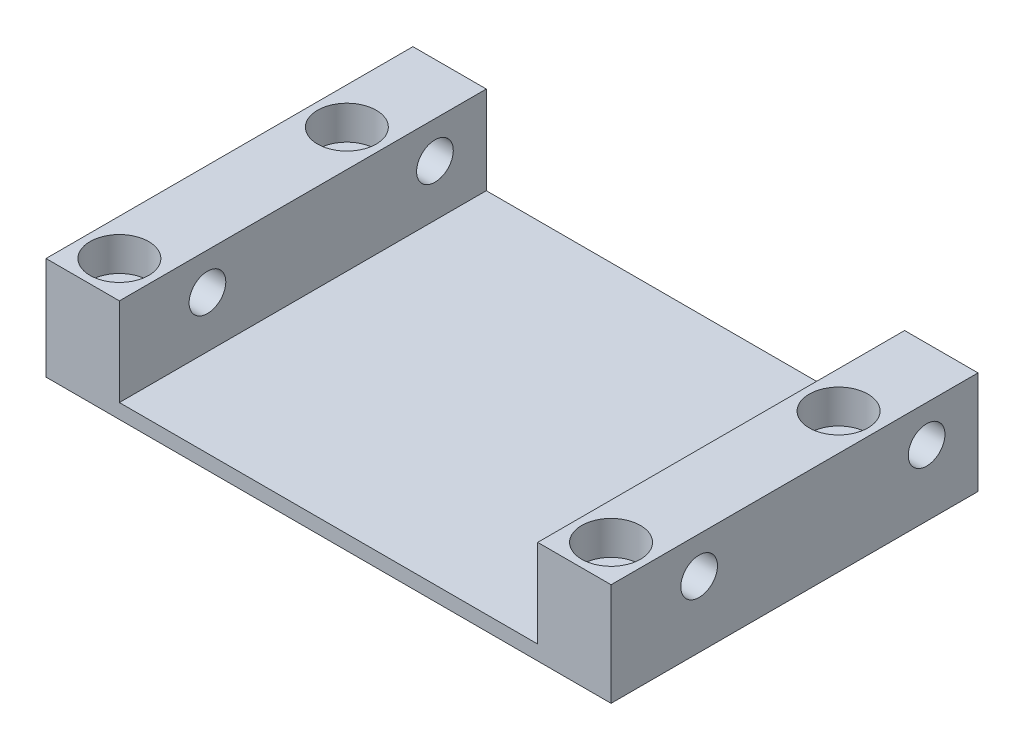
SolidWorks part; units mm, degrees
material "1060 合金"
ref_plane "前视基准面" through (0, 0, 0) normal (0, 0, 1) x (1, 0, 0)
ref_plane "上视基准面" through (0, 0, 0) normal (0, 1, 0) x (1, 0, 0)
ref_plane "右视基准面" through (0, 0, 0) normal (1, 0, 0) x (0, 0, -1)
sketch "草图1" plane through (0, 0, 0) normal (0, 0, 1) x (1, 0, 0)
  line L0 (0, 0) -> (0, 27.6431) construction
  line L3 (-28.5, 2) -> (-28.5, 14)
  line L4 (-28.5, 14) -> (-38.5, 14)
  line L5 (-38.5, 14) -> (-38.5, 0)
  line L10 (38.5, 14) -> (38.5, 0)
  line L11 (28.5, 14) -> (38.5, 14)
  line L12 (28.5, 2) -> (28.5, 14)
  line L13 (-28.5, 2) -> (28.5, 2)
  line L14 (38.5, 0) -> (-38.5, 0)
  dimension "D1" = 57
  dimension "D2" = 2
  dimension "D3" = 12
  dimension "D6" = 10
extrude "凸台-拉伸1" add sketch "草图1" against normal mid plane 50
sketch "草图4" plane through (0, 0, 0) normal (1, 0, 0) x (0, 0, -1)
  line L1 (25, 0) -> (25, 14) construction
  line L2 (25, 14) -> (-25, 14) construction
  circle A0 centre (18, 9) radius 2.5
  circle A2 centre (18, 9) radius 2.5 construction
  circle A4 centre (-13, 9) radius 2.5 construction
  circle A5 centre (-13, 9) radius 2.5
  dimension "D3" = 5
  dimension "D1" = 5
  dimension "D2" = 31
  dimension "D4" = 7
extrude "切除-拉伸1" cut sketch "草图4" against normal mid plane 100
hole_wizard "打孔尺寸根据内六角圆柱头螺钉的类型2" positions "草图10" profile "草图9" counterbore size "M4" standard "GB" end condition through all
sketch "草图10" plane through (0, 14, 0) normal (0, 1, 0) x (-1, 0, 0)
  line L0 (38.5, 13) -> (28.5, 13) construction
  line L1 (38.5, -18) -> (28.5, -18) construction
  line L2 (38.5, -25) -> (38.5, 25) construction
  point P0 (33.5, -11)
  point P1 (33.5, 20)
  dimension "D1" = 7
  dimension "D2" = 7
  dimension "D3" = 5
sketch "草图9" plane through (-33.5, 14, -11) normal (1, 0, 0) x (0, 0, 1)
  line L0 (0, 0) -> (0, 14)
  line L1 (0, 14) -> (2.25, 14)
  line L3 (2.25, 14) -> (2.25, 4.6)
  line L4 (2.25, 4.6) -> (4, 4.6)
  line L5 (4, 4.6) -> (4, 0)
  line L7 (4, 0) -> (0, 0)
  line L11 (0, -6.35) -> (0, 107.95) construction
  dimension "通孔孔直径" = 4.5
  dimension "通孔孔深度" = 14
  dimension "柱形沉头孔直径" = 8
  dimension "柱形沉头孔深度" = 4.6
mirror "镜向2" about plane through (0, 0, 0) normal (1, 0, 0) of "打孔尺寸根据内六角圆柱头螺钉的类型2"
